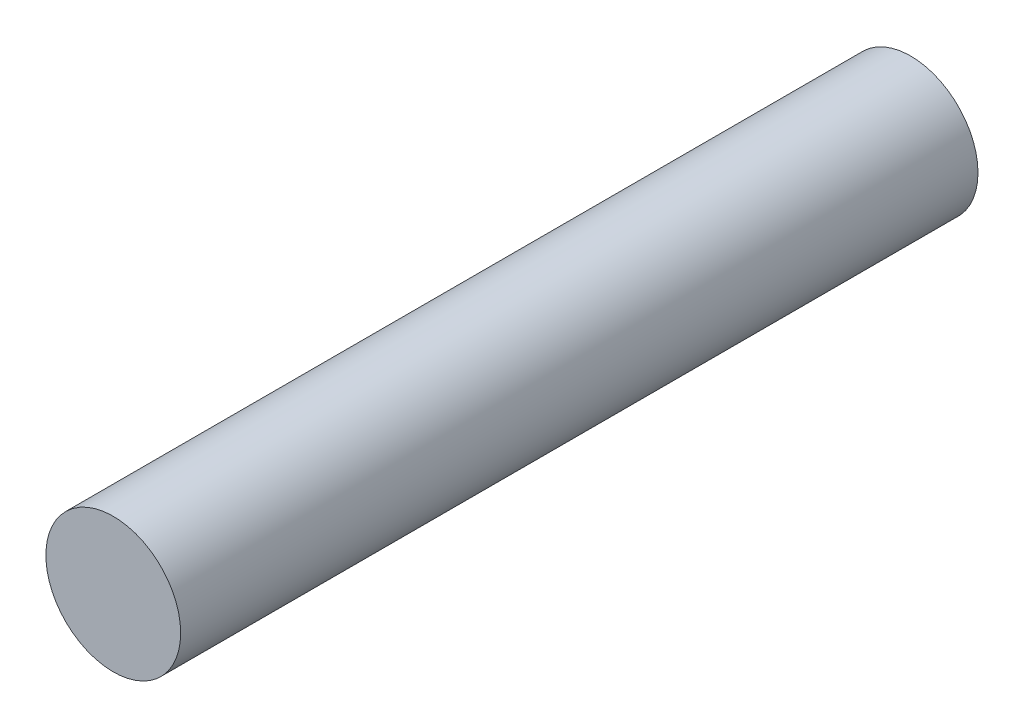
SolidWorks part; units mm, degrees
ref_plane "Front Plane" through (0, 0, 0) normal (0, 0, 1) x (1, 0, 0)
ref_plane "Top Plane" through (0, 0, 0) normal (0, 1, 0) x (1, 0, 0)
ref_plane "Right Plane" through (0, 0, 0) normal (1, 0, 0) x (0, 0, -1)
other "Graphic1"
other "Graphic (Closed) -1"
sketch "Sketch2" plane through (0, 0, 0) normal (0, 0, 1) x (1, 0, 0)
  circle A0 centre (6.2334, 6.2521) radius 2.4936
  point P2 (6.2692, 6.2522)
  point P3 (6.2334, 6.2521)
extrude "Boss-Extrude1" add sketch "Sketch2" along normal blind 29.5
